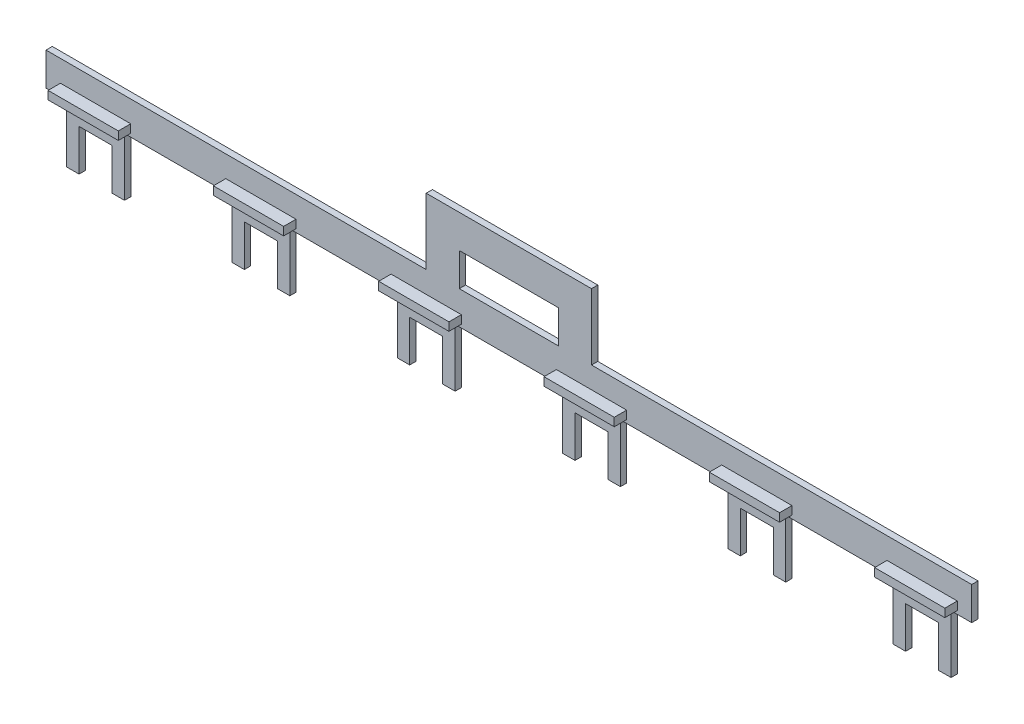
SolidWorks part; units mm, degrees
ref_plane "Front Plane" through (0, 0, 0) normal (0, 0, 1) x (1, 0, 0)
ref_plane "Top Plane" through (0, 0, 0) normal (0, 1, 0) x (1, 0, 0)
ref_plane "Right Plane" through (0, 0, 0) normal (1, 0, 0) x (0, 0, -1)
sketch "Sketch1" plane through (0, 0, 0) normal (0, 0, 1) x (1, 0, 0)
  line L0 (0, 0) -> (0, -2)
  line L1 (0, -2) -> (1.25, -2)
  line L2 (1.25, -2) -> (1.25, -5.5)
  line L3 (1.25, -5.5) -> (4.75, -5.5)
  line L4 (4.75, -5.5) -> (4.75, -2)
  line L5 (4.75, -2) -> (11.25, -2)
  line L6 (11.25, -2) -> (11.25, -5.5)
  line L7 (11.25, -5.5) -> (14.75, -5.5)
  line L8 (14.75, -5.5) -> (14.75, -2)
  line L9 (14.75, -2) -> (21.25, -2)
  line L10 (21.25, -2) -> (21.25, -5.5)
  line L11 (21.25, -5.5) -> (24.75, -5.5)
  line L12 (24.75, -5.5) -> (24.75, -2)
  line L13 (24.75, -2) -> (31.25, -2)
  line L14 (31.25, -2) -> (31.25, -5.5)
  line L15 (31.25, -5.5) -> (34.75, -5.5)
  line L16 (34.75, -5.5) -> (34.75, -2)
  line L17 (34.75, -2) -> (41.25, -2)
  line L18 (41.25, -2) -> (41.25, -5.5)
  line L19 (41.25, -5.5) -> (44.75, -5.5)
  line L20 (44.75, -5.5) -> (44.75, -2)
  line L21 (44.75, -2) -> (51.25, -2)
  line L22 (51.25, -2) -> (51.25, -5.5)
  line L23 (51.25, -5.5) -> (54.75, -5.5)
  line L24 (54.75, -5.5) -> (54.75, -2)
  line L25 (54.75, -2) -> (56, -2)
  line L35 (56, 0) -> (0, 0)
  line L36 (56, 0) -> (56, -2)
  point P29 (3, -5.5)
  point P38 (13, -5.5)
  dimension "D1" = 3.5
  dimension "D2" = 3.5
  dimension "D3" = 10
  dimension "D4" = 2
  dimension "D5" = 1.25
  dimension "D6" = 1.25
extrude "Boss-Extrude1" add sketch "Sketch1" along normal blind 0.38
sketch "Sketch2" plane through (0, 0, 0.38) normal (0, 0, 1) x (1, 0, 0)
  line L0 (23, 0) -> (23, 4)
  line L1 (56, 0) -> (0, 0) construction
  line L2 (23, 4) -> (33, 4)
  line L3 (33, 4) -> (33, 0)
  line L4 (33, 0) -> (31, 0)
  line L5 (31, 0) -> (31, 2)
  line L6 (31, 2) -> (25, 2)
  line L7 (25, 2) -> (25, 0)
  line L8 (25, 0) -> (23, 0)
  line L9 (28, 0) -> (28, 2) construction
  dimension "D1" = 2
  dimension "D2" = 2
  dimension "D3" = 2
  dimension "D4" = 2
  dimension "D5" = 10
extrude "Boss-Extrude2" add sketch "Sketch2" against normal up to surface (0.38 mm away) contours L6 L7 L8 L0 L2 L3 L4 L5 up to face at (28, -3.3571, 0)
sketch "Sketch3" plane through (0, 0, 0.38) normal (0, 0, 1) x (1, 0, 0)
  line L0 (1.25, -5.5) -> (4.75, -5.5) construction
  line L1 (0.875, -1.3) -> (5.125, -1.3)
  line L2 (0.875, -1.3) -> (0.875, -1.8)
  line L3 (0.875, -1.8) -> (5.125, -1.8)
  line L4 (5.125, -1.3) -> (5.125, -1.8)
  line L6 (3, -1.8) -> (3, -5.5) construction
  dimension "D1" = 3.7
  dimension "D2" = 0.5
  dimension "D3" = 4.25
extrude "Boss-Extrude3" add sketch "Sketch3" along normal blind 0.75
pattern_linear "LPattern1" count 6 spacing 10 along (1, 0, 0) of "Boss-Extrude3"
sketch "Sketch4" plane through (0, 0, 0.38) normal (0, 0, 1) x (1, 0, 0)
  line L0 (1.25, -5.5) -> (4.75, -5.5) construction
  line L1 (2, -5.5) -> (4, -5.5)
  line L2 (2, -5.5) -> (2, -3)
  line L3 (2, -3) -> (4, -3)
  line L4 (4, -5.5) -> (4, -3)
  line L5 (11.25, -5.5) -> (14.75, -5.5) construction
  line L6 (12, -5.5) -> (14, -5.5)
  line L7 (12, -5.5) -> (12, -3)
  line L8 (12, -3) -> (14, -3)
  line L9 (14, -5.5) -> (14, -3)
  line L10 (21.25, -5.5) -> (24.75, -5.5) construction
  line L11 (22, -5.5) -> (24, -5.5)
  line L12 (22, -5.5) -> (22, -3)
  line L13 (22, -3) -> (24, -3)
  line L14 (24, -5.5) -> (24, -3)
  line L15 (31.25, -5.5) -> (34.75, -5.5) construction
  line L16 (32, -5.5) -> (34, -5.5)
  line L17 (32, -5.5) -> (32, -3)
  line L18 (32, -3) -> (34, -3)
  line L19 (34, -5.5) -> (34, -3)
  line L20 (41.25, -5.5) -> (44.75, -5.5) construction
  line L21 (42, -5.5) -> (44, -5.5)
  line L22 (42, -5.5) -> (42, -3)
  line L23 (42, -3) -> (44, -3)
  line L24 (44, -5.5) -> (44, -3)
  line L25 (51.25, -5.5) -> (54.75, -5.5) construction
  line L26 (52, -5.5) -> (54, -5.5)
  line L27 (52, -5.5) -> (52, -3)
  line L28 (52, -3) -> (54, -3)
  line L29 (54, -5.5) -> (54, -3)
  line L30 (1.25, -2) -> (1.25, -5.5) construction
  line L31 (0, -2) -> (1.25, -2) construction
  point P36 (3, -5.5)
  point P37 (13, -5.5)
  point P38 (33, -5.5)
  point P39 (23, -5.5)
  point P40 (53, -5.5)
  point P41 (43, -5.5)
  dimension "D1" = 0.75
  dimension "D2" = 1
extrude "Cut-Extrude1" cut sketch "Sketch4" against normal through all both and the other way through all
